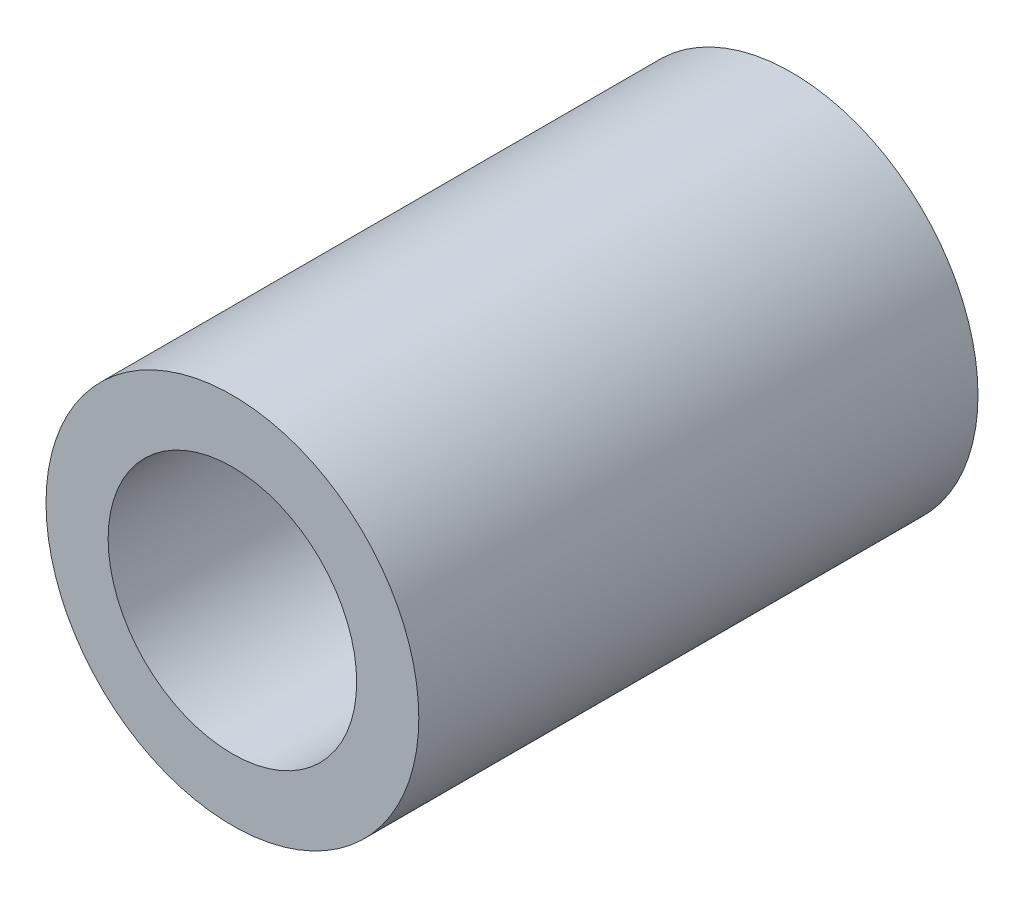
SolidWorks part; units mm, degrees
ref_plane "Front Plane" through (0, 0, 0) normal (0, 0, 1) x (1, 0, 0)
ref_plane "Top Plane" through (0, 0, 0) normal (0, 1, 0) x (1, 0, 0)
ref_plane "Right Plane" through (0, 0, 0) normal (1, 0, 0) x (0, 0, -1)
sketch "Sketch1" plane through (0, 0, 0) normal (0, 0, 1) x (1, 0, 0)
  circle A0 centre (0, 0) radius 2.3813
  circle A1 centre (0, 0) radius 1.5875
  dimension "D1" = 4.7625
  dimension "D2" = 3.175
extrude "Boss-Extrude1" add sketch "Sketch1" along normal blind 7.1437
